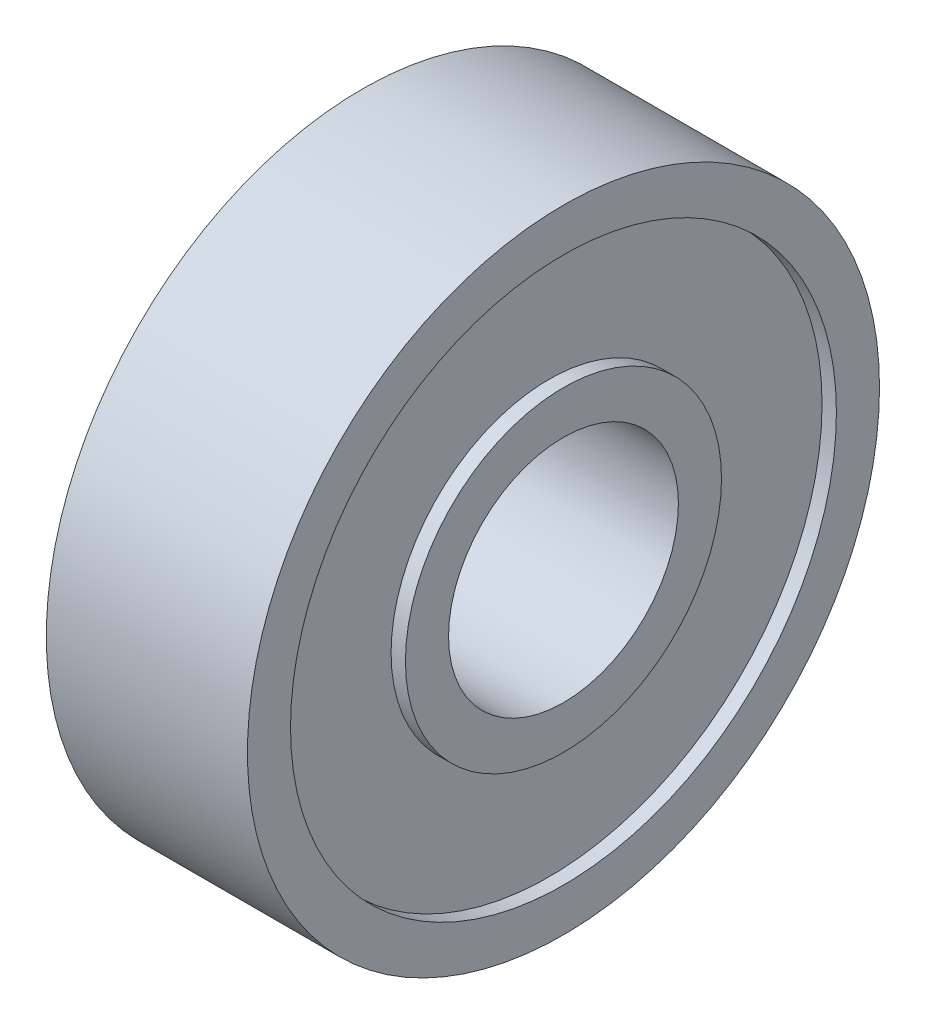
SolidWorks part; units mm, degrees
ref_plane "Plan de face" through (0, 0, 0) normal (0, 0, 1) x (1, 0, 0)
ref_plane "Plan de dessus" through (0, 0, 0) normal (0, 1, 0) x (1, 0, 0)
ref_plane "Plan de droite" through (0, 0, 0) normal (1, 0, 0) x (0, 0, -1)
sketch "Esquisse1" plane through (0, 0, 0) normal (1, 0, 0) x (0, 0, -1)
  circle A0 centre (0, 0) radius 11
  circle A1 centre (0, 0) radius 4
  circle A2 centre (0, 0) radius 9.5
  circle A3 centre (0, 0) radius 5.5
  dimension "D1" = 22
  dimension "D2" = 8
  dimension "D3" = 1.5
  dimension "D4" = 1.5
extrude "Boss.-Extru.1" add sketch "Esquisse1" along normal mid plane 7 contours A0 A1 | A3 A1
sketch "Esquisse2" plane through (0, 0, 0) normal (1, 0, 0) x (0, 0, -1)
  circle A0 centre (0, 0) radius 11
  circle A1 centre (0, 0) radius 5.5
  circle A2 centre (0, 0) radius 5.5 construction
  circle A3 centre (0, 0) radius 11 construction
extrude "Boss.-Extru.2" add sketch "Esquisse2" along normal mid plane 6
equation "\"D4@Esquisse1\"=\"D3@Esquisse1\""
